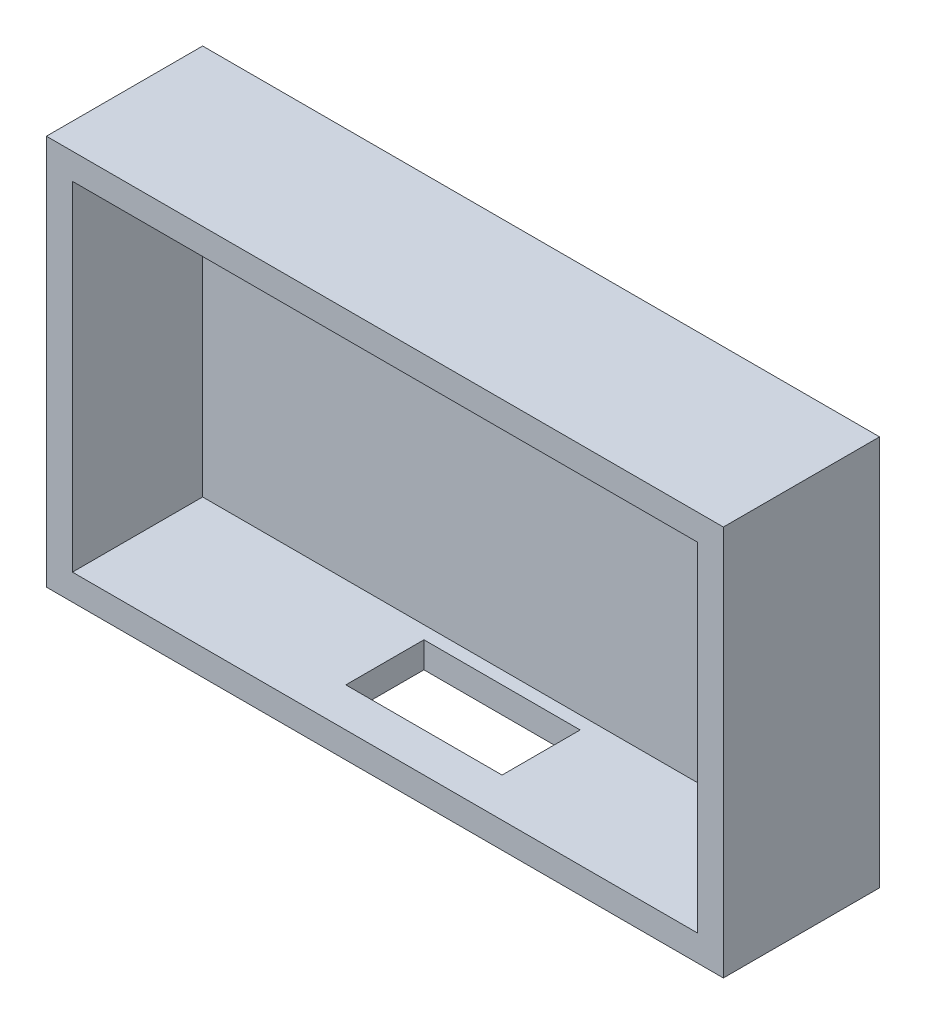
SolidWorks part; units mm, degrees
ref_plane "Front Plane" through (0, 0, 0) normal (0, 0, 1) x (1, 0, 0)
ref_plane "Top Plane" through (0, 0, 0) normal (0, 1, 0) x (1, 0, 0)
ref_plane "Right Plane" through (0, 0, 0) normal (1, 0, 0) x (0, 0, -1)
sketch "Sketch1" plane through (0, 0, 0) normal (0, 1, 0) x (1, 0, 0)
  line L1 (0, 0) -> (130, 0)
  line L2 (0, 0) -> (0, 30)
  line L3 (0, 30) -> (130, 30)
  line L4 (130, 0) -> (130, 30)
  dimension "D1" = 130
  dimension "D2" = 30
extrude "Boss-Extrude1" add sketch "Sketch1" along normal blind 75
shell "Shell1" thickness 5
sketch "Sketch2" plane through (0, 0, 0) normal (0, -1, 0) x (1, 0, 0)
  line L0 (0, -30) -> (130, 0) construction
  line L1 (50, -22.5) -> (80, -22.5)
  line L2 (50, -22.5) -> (50, -7.5)
  line L3 (50, -7.5) -> (80, -7.5)
  line L4 (80, -22.5) -> (80, -7.5)
  line L5 (50, -22.5) -> (80, -7.5) construction
  line L6 (50, -7.5) -> (80, -22.5) construction
  point P0 (65, -15)
  dimension "D1" = 30
  dimension "D2" = 15
extrude "Cut-Extrude1" cut sketch "Sketch2" against normal up to next
